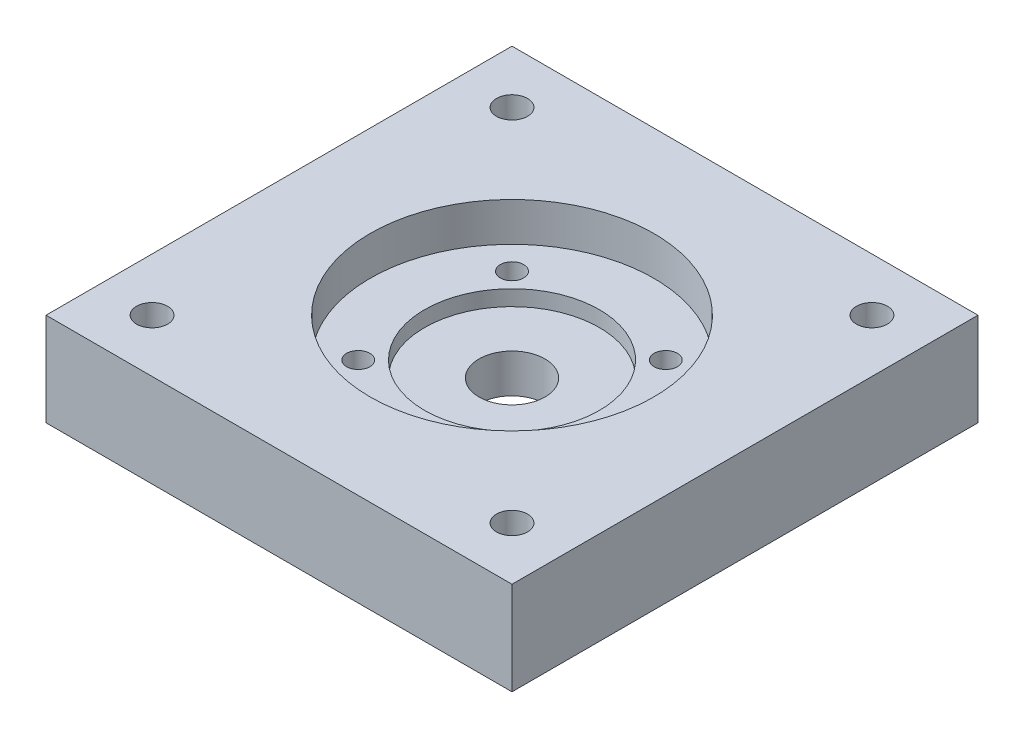
SolidWorks part; units mm, degrees
ref_plane "前视基准面" through (0, 0, 0) normal (0, 0, 1) x (1, 0, 0)
ref_plane "上视基准面" through (0, 0, 0) normal (0, 1, 0) x (1, 0, 0)
ref_plane "右视基准面" through (0, 0, 0) normal (1, 0, 0) x (0, 0, -1)
sketch "草图1" plane through (0, 0, 0) normal (0, 1, 0) x (1, 0, 0)
  line L0 (25.6208, 20.7218) -> (26.5174, 24.0679)
  line L1 (-21.05, 21.05) -> (21.05, 21.05)
  line L2 (-21.05, 21.05) -> (-21.05, -21.05)
  line L3 (-21.05, -21.05) -> (21.05, -21.05)
  line L4 (21.05, 21.05) -> (21.05, -21.05)
  line L5 (-21.05, 21.05) -> (21.05, -21.05) construction
  line L6 (-21.05, -21.05) -> (21.05, 21.05) construction
  line L7 (-30, 30) -> (30, 30)
  line L8 (-30, 30) -> (-30, -30)
  line L9 (-30, -30) -> (30, -30)
  line L10 (30, 30) -> (30, -30)
  line L11 (-30, 30) -> (30, -30) construction
  line L12 (-30, -30) -> (30, 30) construction
  line L13 (-20.7218, 25.6208) -> (-24.0679, 26.5174)
  line L14 (-24.0679, 26.5174) -> (-26.5174, 24.0679)
  line L15 (-26.5174, 24.0679) -> (-25.6208, 20.7218)
  line L16 (-25.6208, 20.7218) -> (-22.2747, 19.8253)
  line L17 (-22.2747, 19.8253) -> (-19.8253, 22.2747)
  line L18 (-19.8253, 22.2747) -> (-20.7218, 25.6208)
  line L19 (26.5174, 24.0679) -> (24.0679, 26.5174)
  line L20 (24.0679, 26.5174) -> (20.7218, 25.6208)
  line L21 (20.7218, 25.6208) -> (19.8253, 22.2747)
  line L22 (19.8253, 22.2747) -> (22.2747, 19.8253)
  line L23 (22.2747, 19.8253) -> (25.6208, 20.7218)
  line L24 (20.7218, -25.6208) -> (24.0679, -26.5174)
  line L25 (24.0679, -26.5174) -> (26.5174, -24.0679)
  line L26 (26.5174, -24.0679) -> (25.6208, -20.7218)
  line L27 (25.6208, -20.7218) -> (22.2747, -19.8253)
  line L28 (22.2747, -19.8253) -> (19.8253, -22.2747)
  line L29 (19.8253, -22.2747) -> (20.7218, -25.6208)
  line L30 (-25.6208, -20.7218) -> (-26.5174, -24.0679)
  line L31 (-26.5174, -24.0679) -> (-24.0679, -26.5174)
  line L32 (-24.0679, -26.5174) -> (-20.7218, -25.6208)
  line L33 (-20.7218, -25.6208) -> (-19.8253, -22.2747)
  line L34 (-19.8253, -22.2747) -> (-22.2747, -19.8253)
  line L35 (-22.2747, -19.8253) -> (-25.6208, -20.7218)
  circle A0 centre (0, 0) radius 14
  circle A1 centre (-9.8995, 9.8995) radius 1.5
  circle A2 centre (9.8995, 9.8995) radius 1.5
  circle A3 centre (9.8995, -9.8995) radius 1.5
  circle A4 centre (-9.8995, -9.8995) radius 1.5
  circle A5 centre (-23.1713, 23.1713) radius 2
  circle A6 centre (23.1713, 23.1713) radius 2
  circle A7 centre (-23.1713, -23.1713) radius 2
  circle A8 centre (23.1713, -23.1713) radius 2
  circle A9 centre (0, 0) radius 18.25
  circle A10 centre (-23.1713, 23.1713) radius 3 construction
  circle A11 centre (0, 0) radius 4.25
  circle A12 centre (0, 0) radius 11.25
  point P56 (0, 0)
  dimension "D1" = 28
  dimension "D3" = 3
  dimension "D5" = 4
  dimension "D6" = 36.5
  dimension "D8" = 3
  dimension "D11" = 8.5
  dimension "D12" = 22.5
  dimension "D2" = 42.1
  dimension "D4" = 60
  dimension "D7" = 6
  dimension "D9" = 45
  dimension "D10" = 4
extrude "凸台-拉伸1" add sketch "草图1" along normal blind 5 contours L10 L7 L8 L9 L35 L34 L2 L17 L16 L15 L14 L13 L18 L1 L22 L21 L20 L19 L0 L23 L4 L28 L27 L26 L25 L24 L29 L3 L33 L32 L31 L30 | L4 L1 L2 L3 A9 | A9 A4 A0 A1 A2 A3 | A4 A0 A3 A2 A1 A12 | A12 A11 | L17 L18 L13 L14 L15 L16 A5 | L22 L23 L0 L19 L20 L21 A6 | L34 L35 L30 L31 L32 L33 A7 | L28 L29 L24 L25 L26 L27 A8
sketch "草图2" plane through (0, 5, 0) normal (0, 1, 0) x (1, 0, 0)
  line L4 (21.05, 21.05) -> (-21.05, 21.05)
  line L5 (21.05, -21.05) -> (21.05, 21.05)
  line L6 (-21.05, -21.05) -> (21.05, -21.05)
  line L7 (-21.05, 21.05) -> (-21.05, -21.05)
  line L8 (21.05, 21.05) -> (-21.05, 21.05)
  line L9 (21.05, -21.05) -> (21.05, 21.05)
  line L10 (-21.05, -21.05) -> (21.05, -21.05)
  line L11 (-21.05, 21.05) -> (-21.05, -21.05)
  line L12 (30, 30) -> (-30, 30)
  line L13 (30, -30) -> (30, 30)
  line L14 (-30, -30) -> (30, -30)
  line L15 (-30, 30) -> (-30, -30)
  line L16 (30, 30) -> (-30, 30)
  line L17 (30, -30) -> (30, 30)
  line L18 (-30, -30) -> (30, -30)
  line L19 (-30, 30) -> (-30, -30)
  line L22 (-25.6208, 20.7218) -> (-22.2747, 19.8253)
  line L23 (-22.2747, 19.8253) -> (-19.8253, 22.2747)
  line L24 (-19.8253, 22.2747) -> (-20.7218, 25.6208)
  line L25 (-20.7218, 25.6208) -> (-24.0679, 26.5174)
  line L26 (-24.0679, 26.5174) -> (-26.5174, 24.0679)
  line L27 (-26.5174, 24.0679) -> (-25.6208, 20.7218)
  line L28 (-25.6208, 20.7218) -> (-22.2747, 19.8253)
  line L29 (-22.2747, 19.8253) -> (-19.8253, 22.2747)
  line L30 (-19.8253, 22.2747) -> (-20.7218, 25.6208)
  line L31 (-20.7218, 25.6208) -> (-24.0679, 26.5174)
  line L32 (-24.0679, 26.5174) -> (-26.5174, 24.0679)
  line L33 (-26.5174, 24.0679) -> (-25.6208, 20.7218)
  line L34 (25.6208, 20.7218) -> (26.5174, 24.0679)
  line L35 (26.5174, 24.0679) -> (24.0679, 26.5174)
  line L36 (24.0679, 26.5174) -> (20.7218, 25.6208)
  line L37 (20.7218, 25.6208) -> (19.8253, 22.2747)
  line L38 (19.8253, 22.2747) -> (22.2747, 19.8253)
  line L39 (22.2747, 19.8253) -> (25.6208, 20.7218)
  line L40 (25.6208, 20.7218) -> (26.5174, 24.0679)
  line L41 (26.5174, 24.0679) -> (24.0679, 26.5174)
  line L42 (24.0679, 26.5174) -> (20.7218, 25.6208)
  line L43 (20.7218, 25.6208) -> (19.8253, 22.2747)
  line L44 (19.8253, 22.2747) -> (22.2747, 19.8253)
  line L45 (22.2747, 19.8253) -> (25.6208, 20.7218)
  line L46 (-25.6208, -20.7218) -> (-26.5174, -24.0679)
  line L47 (-26.5174, -24.0679) -> (-24.0679, -26.5174)
  line L48 (-24.0679, -26.5174) -> (-20.7218, -25.6208)
  line L49 (-20.7218, -25.6208) -> (-19.8253, -22.2747)
  line L50 (-19.8253, -22.2747) -> (-22.2747, -19.8253)
  line L51 (-22.2747, -19.8253) -> (-25.6208, -20.7218)
  line L52 (-25.6208, -20.7218) -> (-26.5174, -24.0679)
  line L53 (-26.5174, -24.0679) -> (-24.0679, -26.5174)
  line L54 (-24.0679, -26.5174) -> (-20.7218, -25.6208)
  line L55 (-20.7218, -25.6208) -> (-19.8253, -22.2747)
  line L56 (-19.8253, -22.2747) -> (-22.2747, -19.8253)
  line L57 (-22.2747, -19.8253) -> (-25.6208, -20.7218)
  line L58 (22.2747, -19.8253) -> (19.8253, -22.2747)
  line L59 (19.8253, -22.2747) -> (20.7218, -25.6208)
  line L60 (20.7218, -25.6208) -> (24.0679, -26.5174)
  line L61 (24.0679, -26.5174) -> (26.5174, -24.0679)
  line L62 (26.5174, -24.0679) -> (25.6208, -20.7218)
  line L63 (25.6208, -20.7218) -> (22.2747, -19.8253)
  line L64 (22.2747, -19.8253) -> (19.8253, -22.2747)
  line L65 (19.8253, -22.2747) -> (20.7218, -25.6208)
  line L66 (20.7218, -25.6208) -> (24.0679, -26.5174)
  line L67 (24.0679, -26.5174) -> (26.5174, -24.0679)
  line L68 (26.5174, -24.0679) -> (25.6208, -20.7218)
  line L69 (25.6208, -20.7218) -> (22.2747, -19.8253)
  circle A1 centre (-9.8995, -9.8995) radius 1.5
  circle A2 centre (-9.8995, -9.8995) radius 1.5
  circle A3 centre (9.8995, -9.8995) radius 1.5
  circle A4 centre (9.8995, -9.8995) radius 1.5
  circle A5 centre (9.8995, 9.8995) radius 1.5
  circle A6 centre (9.8995, 9.8995) radius 1.5
  circle A7 centre (-9.8995, 9.8995) radius 1.5
  circle A8 centre (-9.8995, 9.8995) radius 1.5
  circle A9 centre (0, 0) radius 14
  circle A10 centre (0, 0) radius 14
  circle A11 centre (0, 0) radius 4.25
  circle A12 centre (0, 0) radius 4.25
  circle A13 centre (0, 0) radius 18.25
  circle A14 centre (0, 0) radius 18.25
  circle A15 centre (23.1713, -23.1713) radius 2
  circle A16 centre (23.1713, -23.1713) radius 2
  circle A17 centre (-23.1713, -23.1713) radius 2
  circle A18 centre (-23.1713, -23.1713) radius 2
  circle A19 centre (23.1713, 23.1713) radius 2
  circle A20 centre (23.1713, 23.1713) radius 2
  circle A21 centre (-23.1713, 23.1713) radius 2
  circle A22 centre (-23.1713, 23.1713) radius 2
  circle A23 centre (0, 0) radius 11.25
  circle A24 centre (0, 0) radius 11.25
  circle M45 centre (-9.8995, -9.8995) radius 1.5
  circle M46 centre (-9.8995, 9.8995) radius 1.5
  circle M47 centre (9.8995, 9.8995) radius 1.5
  line M48 (30, -30) -> (30, 30)
  line M49 (30, 30) -> (-30, 30)
  line M50 (-30, 30) -> (-30, -30)
  line M51 (-30, -30) -> (30, -30)
  circle M56 centre (9.8995, -9.8995) radius 1.5
  dimension "D1" = 0
  dimension "D2" = 0
  dimension "D3" = 0
  dimension "D4" = 0
  dimension "D5" = 0
  dimension "D6" = 0
  dimension "D7" = 0
  dimension "D8" = 0
  dimension "D9" = 0
  dimension "D10" = 0
  dimension "D11" = 0
  dimension "D12" = 0
  dimension "D13" = 0
  dimension "D14" = 0
  dimension "D15" = 0
  dimension "D16" = 0
  dimension "D17" = 0
  dimension "D18" = 0
extrude "凸台-拉伸2" add sketch "草图2" along normal blind 2 contours L69 L68 L67 L66 L65 L64 L10 L56 L55 L54 L53 L52 L57 L11 L29 L28 L33 L32 L31 L30 L8 L44 L43 L42 L41 L40 L45 L9 M51 M48 M49 M50 | L8 L11 L10 L9 A14 | A10 A6 A8 A24 M56 M45 | A14 A10 A4 A2 M46 M47 | A20 | A16 | A18 | A22
sketch "草图3" plane through (0, 7, 0) normal (0, 1, 0) x (1, 0, 0)
  line L4 (21.05, 21.05) -> (-21.05, 21.05)
  line L5 (21.05, -21.05) -> (21.05, 21.05)
  line L6 (-21.05, -21.05) -> (21.05, -21.05)
  line L7 (-21.05, 21.05) -> (-21.05, -21.05)
  line L8 (21.05, 21.05) -> (-21.05, 21.05)
  line L9 (21.05, -21.05) -> (21.05, 21.05)
  line L10 (-21.05, -21.05) -> (21.05, -21.05)
  line L11 (-21.05, 21.05) -> (-21.05, -21.05)
  line L12 (30, 30) -> (-30, 30)
  line L13 (30, -30) -> (30, 30)
  line L14 (-30, -30) -> (30, -30)
  line L15 (-30, 30) -> (-30, -30)
  line L16 (30, 30) -> (-30, 30)
  line L17 (30, -30) -> (30, 30)
  line L18 (-30, -30) -> (30, -30)
  line L19 (-30, 30) -> (-30, -30)
  line L22 (-25.6208, 20.7218) -> (-22.2747, 19.8253)
  line L23 (-22.2747, 19.8253) -> (-19.8253, 22.2747)
  line L24 (-19.8253, 22.2747) -> (-20.7218, 25.6208)
  line L25 (-20.7218, 25.6208) -> (-24.0679, 26.5174)
  line L26 (-24.0679, 26.5174) -> (-26.5174, 24.0679)
  line L27 (-26.5174, 24.0679) -> (-25.6208, 20.7218)
  line L28 (-25.6208, 20.7218) -> (-22.2747, 19.8253)
  line L29 (-22.2747, 19.8253) -> (-19.8253, 22.2747)
  line L30 (-19.8253, 22.2747) -> (-20.7218, 25.6208)
  line L31 (-20.7218, 25.6208) -> (-24.0679, 26.5174)
  line L32 (-24.0679, 26.5174) -> (-26.5174, 24.0679)
  line L33 (-26.5174, 24.0679) -> (-25.6208, 20.7218)
  line L34 (25.6208, 20.7218) -> (26.5174, 24.0679)
  line L35 (26.5174, 24.0679) -> (24.0679, 26.5174)
  line L36 (24.0679, 26.5174) -> (20.7218, 25.6208)
  line L37 (20.7218, 25.6208) -> (19.8253, 22.2747)
  line L38 (19.8253, 22.2747) -> (22.2747, 19.8253)
  line L39 (22.2747, 19.8253) -> (25.6208, 20.7218)
  line L40 (25.6208, 20.7218) -> (26.5174, 24.0679)
  line L41 (26.5174, 24.0679) -> (24.0679, 26.5174)
  line L42 (24.0679, 26.5174) -> (20.7218, 25.6208)
  line L43 (20.7218, 25.6208) -> (19.8253, 22.2747)
  line L44 (19.8253, 22.2747) -> (22.2747, 19.8253)
  line L45 (22.2747, 19.8253) -> (25.6208, 20.7218)
  line L46 (-25.6208, -20.7218) -> (-26.5174, -24.0679)
  line L47 (-26.5174, -24.0679) -> (-24.0679, -26.5174)
  line L48 (-24.0679, -26.5174) -> (-20.7218, -25.6208)
  line L49 (-20.7218, -25.6208) -> (-19.8253, -22.2747)
  line L50 (-19.8253, -22.2747) -> (-22.2747, -19.8253)
  line L51 (-22.2747, -19.8253) -> (-25.6208, -20.7218)
  line L52 (-25.6208, -20.7218) -> (-26.5174, -24.0679)
  line L53 (-26.5174, -24.0679) -> (-24.0679, -26.5174)
  line L54 (-24.0679, -26.5174) -> (-20.7218, -25.6208)
  line L55 (-20.7218, -25.6208) -> (-19.8253, -22.2747)
  line L56 (-19.8253, -22.2747) -> (-22.2747, -19.8253)
  line L57 (-22.2747, -19.8253) -> (-25.6208, -20.7218)
  line L58 (22.2747, -19.8253) -> (19.8253, -22.2747)
  line L59 (19.8253, -22.2747) -> (20.7218, -25.6208)
  line L60 (20.7218, -25.6208) -> (24.0679, -26.5174)
  line L61 (24.0679, -26.5174) -> (26.5174, -24.0679)
  line L62 (26.5174, -24.0679) -> (25.6208, -20.7218)
  line L63 (25.6208, -20.7218) -> (22.2747, -19.8253)
  line L64 (22.2747, -19.8253) -> (19.8253, -22.2747)
  line L65 (19.8253, -22.2747) -> (20.7218, -25.6208)
  line L66 (20.7218, -25.6208) -> (24.0679, -26.5174)
  line L67 (24.0679, -26.5174) -> (26.5174, -24.0679)
  line L68 (26.5174, -24.0679) -> (25.6208, -20.7218)
  line L69 (25.6208, -20.7218) -> (22.2747, -19.8253)
  circle A1 centre (-9.8995, -9.8995) radius 1.5
  circle A2 centre (-9.8995, -9.8995) radius 1.5
  circle A3 centre (9.8995, -9.8995) radius 1.5
  circle A4 centre (9.8995, -9.8995) radius 1.5
  circle A5 centre (9.8995, 9.8995) radius 1.5
  circle A6 centre (9.8995, 9.8995) radius 1.5
  circle A7 centre (-9.8995, 9.8995) radius 1.5
  circle A8 centre (-9.8995, 9.8995) radius 1.5
  circle A9 centre (0, 0) radius 14
  circle A10 centre (0, 0) radius 14
  circle A11 centre (0, 0) radius 4.25
  circle A12 centre (0, 0) radius 4.25
  circle A13 centre (0, 0) radius 18.25
  circle A14 centre (0, 0) radius 18.25
  circle A15 centre (23.1713, -23.1713) radius 2
  circle A16 centre (23.1713, -23.1713) radius 2
  circle A17 centre (-23.1713, -23.1713) radius 2
  circle A18 centre (-23.1713, -23.1713) radius 2
  circle A19 centre (23.1713, 23.1713) radius 2
  circle A20 centre (23.1713, 23.1713) radius 2
  circle A21 centre (-23.1713, 23.1713) radius 2
  circle A22 centre (-23.1713, 23.1713) radius 2
  circle A23 centre (0, 0) radius 11.25
  circle A24 centre (0, 0) radius 11.25
  dimension "D1" = 0
  dimension "D2" = 0
  dimension "D3" = 0
  dimension "D4" = 0
  dimension "D5" = 0
  dimension "D6" = 0
  dimension "D7" = 0
  dimension "D8" = 0
  dimension "D9" = 0
  dimension "D10" = 0
  dimension "D11" = 0
  dimension "D12" = 0
  dimension "D13" = 0
  dimension "D14" = 0
  dimension "D15" = 0
  dimension "D16" = 0
  dimension "D17" = 0
  dimension "D18" = 0
extrude "凸台-拉伸3" add sketch "草图3" along normal blind 5
